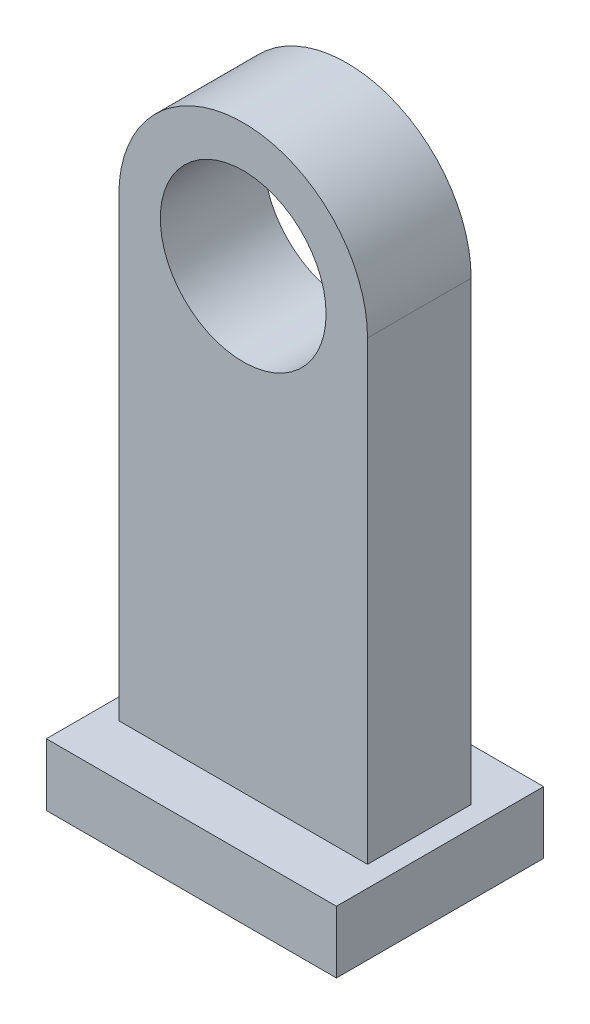
SolidWorks part; units mm, degrees
ref_plane "Front Plane" through (0, 0, 0) normal (0, 0, 1) x (1, 0, 0)
ref_plane "Top Plane" through (0, 0, 0) normal (0, 1, 0) x (1, 0, 0)
ref_plane "Right Plane" through (0, 0, 0) normal (1, 0, 0) x (0, 0, -1)
sketch "Sketch1" plane through (0, 0, 0) normal (0, 0, 1) x (1, 0, 0)
  circle A0 centre (0, 0) radius 4
  circle A1 centre (0, 0) radius 6
  dimension "D1" = 8
  dimension "D2" = 12
extrude "Boss-Extrude1" add sketch "Sketch1" along normal blind 5
sketch "Sketch2" plane through (0, 0, 0) normal (0, 1, 0) x (1, 0, 0)
  line L0 (-6, -5) -> (-6, 0)
  line L1 (-6, 0) -> (6, 0)
  line L2 (6, 0) -> (6, -5)
  line L3 (6, -5) -> (-6, -5)
extrude "Boss-Extrude2" add sketch "Sketch2" against normal blind 22
sketch "Sketch5" plane through (0, 0, 5) normal (0, 0, 1) x (1, 0, 0)
  circle A0 centre (0, 0) radius 4
  dimension "D1" = 8
extrude "Cut-Extrude1" cut sketch "Sketch5" against normal through all both and the other way through all
sketch "Sketch6" plane through (0, -22, 0) normal (0, -1, 0) x (1, 0, 0)
  line L0 (0, 5) -> (0, 0) construction
  line L1 (-6, 5) -> (6, 5) construction
  line L2 (-6, 2.5) -> (6, 2.5) construction
  line L3 (-6, 0) -> (-6, 5) construction
  line L4 (6, 5) -> (6, 0) construction
  line L5 (-7, -2.5) -> (-7, 7.5)
  line L6 (-7, 7.5) -> (7, 7.5)
  line L7 (7, 7.5) -> (7, -2.5)
  line L8 (7, -2.5) -> (-7, -2.5)
  dimension "D1" = 5
  dimension "D2" = 10
  dimension "D3" = 7
  dimension "D4" = 14
extrude "Boss-Extrude3" add sketch "Sketch6" along normal blind 3
